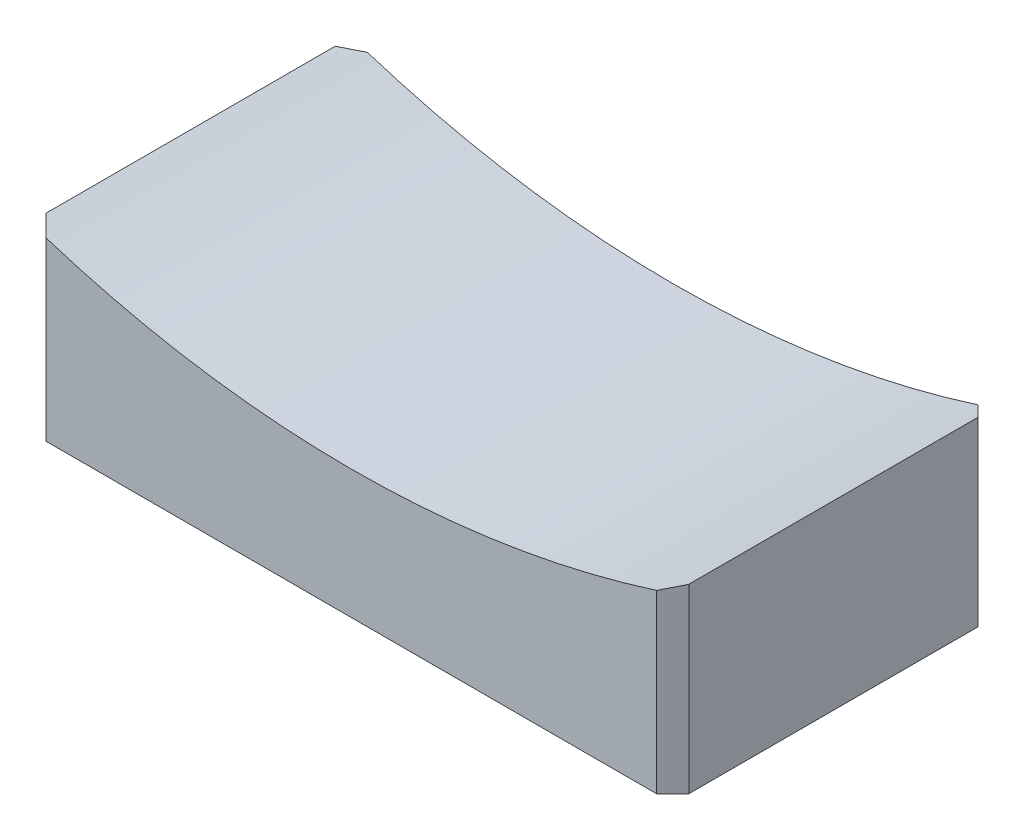
SolidWorks part; units mm, degrees
ref_plane "Front Plane" through (0, 0, 0) normal (0, 0, 1) x (1, 0, 0)
ref_plane "Top Plane" through (0, 0, 0) normal (0, 1, 0) x (1, 0, 0)
ref_plane "Right Plane" through (0, 0, 0) normal (1, 0, 0) x (0, 0, -1)
sketch "Sketch1" plane through (0, 0, 0) normal (0, 0, 1) x (1, 0, 0)
  line L0 (-12.7, 7.1704) -> (-12.7, 0)
  line L1 (-12.7, 0) -> (12.7, 0)
  line L2 (12.7, 0) -> (12.7, 7.1704)
  arc A0 (12.7, 7.1704) -> (-12.7, 7.1704) centre (0, 44.704) cw
  point P6 (0, 5.08)
  point P7 (36.9266, 7.1704)
  dimension "D1" = 39.624
  dimension "D2" = 5.08
  dimension "D3" = 25.4
extrude "Boss-Extrude1" add sketch "Sketch1" along normal blind 12.7
chamfer "Chamfer1" distance 0.635 angle 45 4 edges at (-12.7, 3.5852, 0) (-12.7, 3.5852, 12.7) (12.7, 3.5852, 0) (12.7, 3.5852, 12.7)
